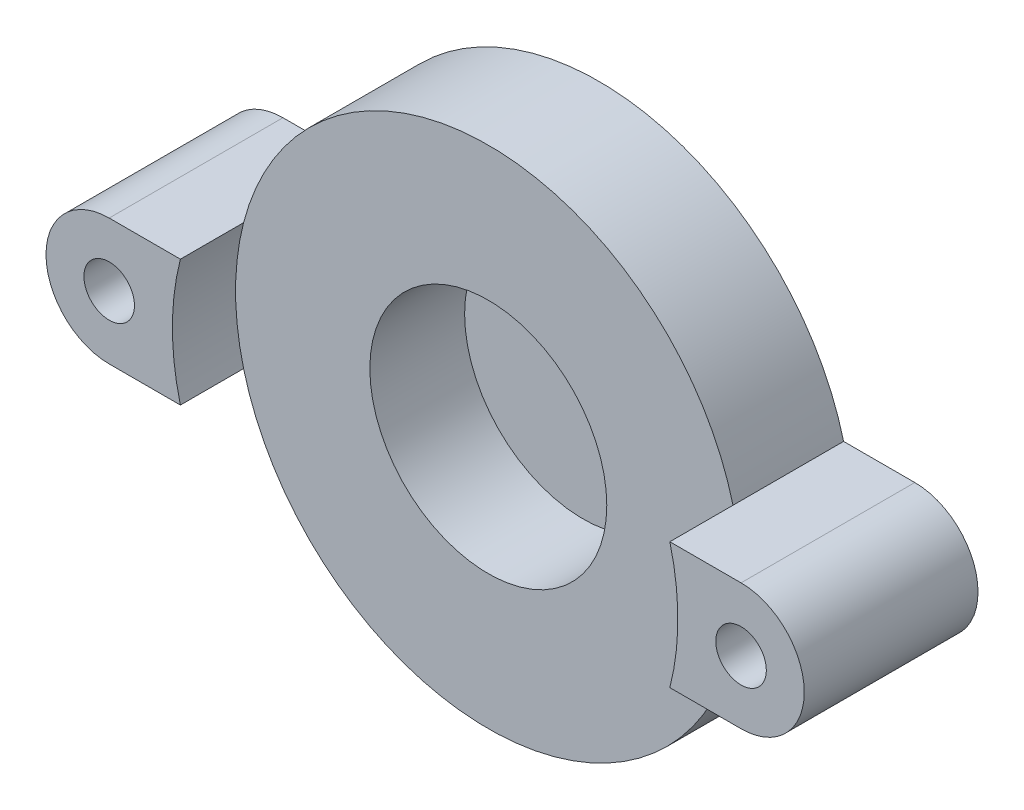
SolidWorks part; units mm, degrees
material "PET"
ref_plane "Front Plane" through (0, 0, 0) normal (0, 0, 1) x (1, 0, 0)
ref_plane "Top Plane" through (0, 0, 0) normal (0, 1, 0) x (1, 0, 0)
ref_plane "Right Plane" through (0, 0, 0) normal (1, 0, 0) x (0, 0, -1)
sketch "Sketch1" plane through (0, 0, 0) normal (0, 0, 1) x (1, 0, 0)
  line L0 (0, 0) -> (0, 27.0971) construction
  line L1 (20, -4) -> (15.4919, -4)
  line L2 (20, 4) -> (15.4919, 4)
  line L5 (-20, 4) -> (-15.4919, 4)
  line L12 (-20, -4) -> (-15.4919, -4)
  circle A0 centre (0, 0) radius 7.5
  circle A1 centre (20, 0) radius 1.6
  arc A2 (20, 4) -> (20, -4) centre (20, 0) cw
  circle A3 centre (0, 0) radius 16
  circle A5 centre (-20, 0) radius 1.6
  arc A6 (-20, 4) -> (-20, -4) centre (-20, 0) ccw
  dimension "D1" = 15
  dimension "D2" = 32
  dimension "D12" = 3.2
  dimension "D13" = 8
  dimension "D14" = 20
extrude "Boss-Extrude1" add sketch "Sketch1" along normal blind 2 contours L0 A3 A0 | A3 L0 A0
sketch "Sketch2" plane through (0, 0, 0) normal (0, 0, 1) x (1, 0, 0)
  line L0 (0, 0) -> (0, 27.0971) construction
  line L1 (20, -4) -> (15.4919, -4)
  line L2 (20, 4) -> (15.4919, 4)
  line L5 (-20, 4) -> (-15.4919, 4)
  line L12 (-20, -4) -> (-15.4919, -4)
  circle A0 centre (0, 0) radius 7.5
  circle A1 centre (20, 0) radius 1.6
  arc A2 (20, 4) -> (20, -4) centre (20, 0) cw
  circle A3 centre (0, 0) radius 16
  circle A5 centre (-20, 0) radius 1.6
  arc A6 (-20, 4) -> (-20, -4) centre (-20, 0) ccw
  dimension "D1" = 15
  dimension "D2" = 32
  dimension "D12" = 3.2
  dimension "D13" = 8
  dimension "D14" = 20
extrude "Boss-Extrude3" add sketch "Sketch2" along normal blind 6 contours L5 A6 L12 A3 A5 | A3 L1 A2 L2 A1
sketch "Sketch5" plane through (0, 0, 0) normal (0, 0, -1) x (-1, 0, 0)
  circle A0 centre (0, 0) radius 16
  arc A1 (15.4919, 4) -> (-15.4919, 4) centre (0, 0) ccw construction
  circle A2 centre (0, 0) radius 7.5
  circle A3 centre (0, 0) radius 7.5 construction
extrude "Boss-Extrude4" add sketch "Sketch5" along normal blind 4
sketch "Sketch6" plane through (0, 0, -4) normal (0, 0, -1) x (-1, 0, 0)
  circle A0 centre (0, 0) radius 16
  circle A1 centre (0, 0) radius 16 construction
extrude "Boss-Extrude7" add sketch "Sketch6" along normal blind 1
sketch "Sketch7" plane through (0, 0, 0) normal (0, 0, 1) x (1, 0, 0)
  line L0 (0, 0) -> (0, 27.0971) construction
  line L1 (20, -4) -> (15.4919, -4)
  line L2 (20, 4) -> (15.4919, 4)
  line L5 (-20, 4) -> (-15.4919, 4)
  line L12 (-20, -4) -> (-15.4919, -4)
  circle A0 centre (0, 0) radius 7.5
  circle A1 centre (20, 0) radius 1.6
  arc A2 (20, 4) -> (20, -4) centre (20, 0) cw
  circle A3 centre (0, 0) radius 16
  circle A5 centre (-20, 0) radius 1.6
  arc A6 (-20, 4) -> (-20, -4) centre (-20, 0) ccw
  dimension "D1" = 15
  dimension "D2" = 32
  dimension "D12" = 3.2
  dimension "D13" = 8
  dimension "D14" = 20
extrude "Boss-Extrude8" add sketch "Sketch7" against normal blind 5 contours A3 L1 A2 L2 A1 | L5 A6 L12 A3 A5
